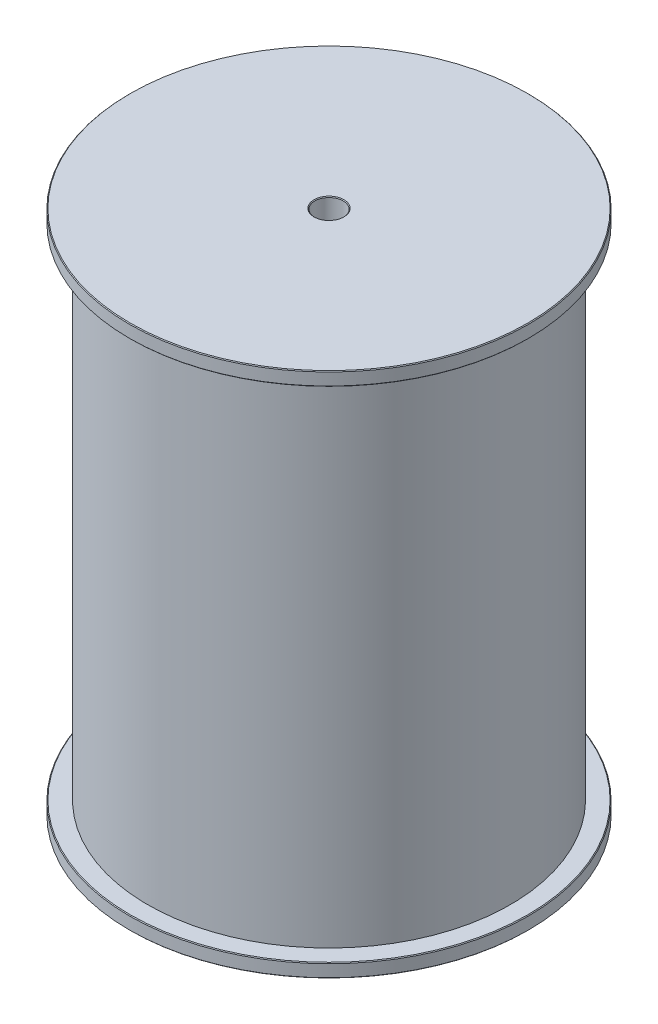
SolidWorks part; units mm, degrees
material "6061-T6 (SS)"
ref_plane "Front Plane" through (0, 0, 0) normal (0, 0, 1) x (1, 0, 0)
ref_plane "Top Plane" through (0, 0, 0) normal (0, 1, 0) x (1, 0, 0)
ref_plane "Right Plane" through (0, 0, 0) normal (1, 0, 0) x (0, 0, -1)
sketch "Sketch1" plane through (0, 0, 0) normal (0, 0, 1) x (1, 0, 0)
  line L0 (2.4892, 0) -> (34.925, 0)
  line L1 (34.925, 0) -> (34.925, 2.3813)
  line L2 (34.925, 2.3813) -> (31.75, 2.3813)
  line L3 (31.75, 2.3813) -> (31.75, 89.6938)
  line L4 (31.75, 89.6938) -> (34.925, 89.6938)
  line L5 (34.925, 89.6938) -> (34.925, 92.075)
  line L6 (34.925, 92.075) -> (2.4892, 92.075)
  line L7 (0, 92.075) -> (0, 0) construction
  line L8 (2.4892, 0) -> (2.4892, 46.0375)
  line L10 (2.4892, 4.7752) -> (2.4892, 36.4998)
  line L12 (2.4892, 46.0375) -> (2.4892, 92.075)
  line L13 (2.4892, 92.075) -> (0, 92.075) construction
  line L14 (0, 0) -> (2.4892, 0) construction
  dimension "D1" = 63.5
  dimension "D2" = 69.85
  dimension "D3" = 87.3125
  dimension "D4" = 92.075
  dimension "D5" = 4.9784
  dimension "D7" = 4.9784
revolve "Revolve1" add sketch "Sketch1" angle 360 about L7
chamfer "Chamfer1" distance 0.127 angle 45 6 edges at (-34.925, 89.6938, 0) (-34.925, 2.3813, 0) (-2.4892, 0, 0) (-34.925, 0, 0) (-34.925, 92.075, 0) (-2.4892, 92.075, 0)
